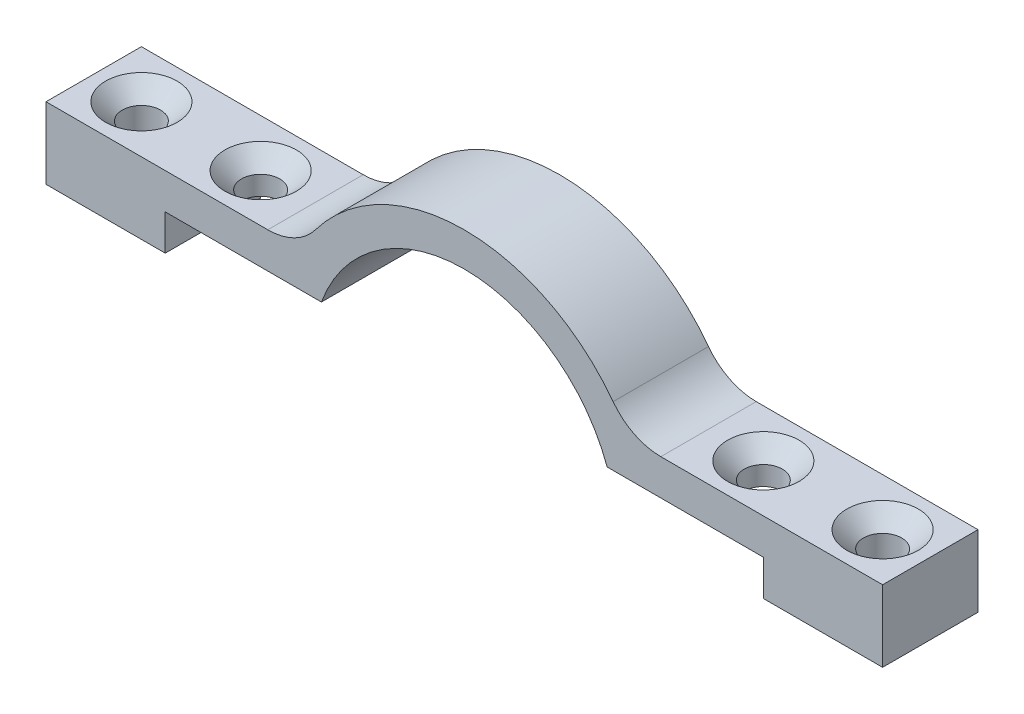
SolidWorks part; units mm, degrees
ref_plane "Front Plane" through (0, 0, 0) normal (0, 0, 1) x (1, 0, 0)
ref_plane "Top Plane" through (0, 0, 0) normal (0, 1, 0) x (1, 0, 0)
ref_plane "Right Plane" through (0, 0, 0) normal (1, 0, 0) x (0, 0, -1)
sketch "Sketch1" plane through (0, 0, 0) normal (0, 0, 1) x (1, 0, 0)
  line L0 (23.6887, 0) -> (-23.6887, 0) construction
  line L1 (-11.9811, 4.3608) -> (0, 0) construction
  line L2 (0, 0) -> (11.9811, 4.3608) construction
  line L3 (-14.9781, 4.3608) -> (-11.9811, 4.3608)
  line L4 (11.9811, 4.3608) -> (14.9781, 4.3608)
  line L5 (-14.9781, 4.3608) -> (-25.0781, 4.3608)
  line L6 (-25.0781, 4.3608) -> (-25.0781, 7.3608)
  line L7 (-25.0781, 7.3608) -> (-13.7542, 7.3608)
  line L8 (14.9781, 4.3608) -> (25.0781, 4.3608)
  line L9 (25.0781, 4.3608) -> (25.0781, 7.3608)
  line L10 (25.0781, 7.3608) -> (13.7542, 7.3608)
  line L11 (-25.0781, 4.3608) -> (-25.0781, 1.3608)
  line L12 (-25.0781, 1.3608) -> (-35.0781, 1.3608)
  line L13 (-35.0781, 1.3608) -> (-35.0781, 7.3608)
  line L16 (-35.0781, 7.3608) -> (-25.0781, 7.3608)
  line L17 (25.0781, 4.3608) -> (25.0781, 1.3608)
  line L18 (25.0781, 1.3608) -> (35.0781, 1.3608)
  line L19 (35.0781, 1.3608) -> (35.0781, 7.3608)
  line L22 (35.0781, 7.3608) -> (25.0781, 7.3608)
  arc A0 (11.9811, 4.3608) -> (-11.9811, 4.3608) centre (0, 0) ccw
  arc A1 (14.9781, 4.3608) -> (-14.9781, 4.3608) centre (0, 0) ccw
  point P4 (0, 0)
  dimension "D2" = 12.75
  dimension "D6" = 15.6
  dimension "D1" = 20
  dimension "D3" = 20
  dimension "D4" = 10.1
  dimension "D5" = 10.1
  dimension "D7" = 3
  dimension "D8" = 3
  dimension "D9" = 3
  dimension "D11" = 10
  dimension "D13" = 3
  dimension "D14" = 10
extrude "Boss-Extrude1" add sketch "Sketch1" along normal blind 8
sketch "Sketch2" plane through (0, 7.3608, 0) normal (0, 1, 0) x (1, 0, 0)
  line L0 (-21.0781, 0) -> (-21.0781, -8) construction
  line L1 (-35.0781, -8) -> (-35.0781, 0) construction
  line L2 (35.0781, -8) -> (35.0781, 0) construction
  line L4 (21.0781, 0) -> (21.0781, -8) construction
  line L10 (-35.0781, -8) -> (-13.7542, -8) construction
  line L11 (-35.0781, 0) -> (-13.7542, 0) construction
  line L12 (35.0781, -8) -> (13.7542, -8) construction
  line L13 (35.0781, 0) -> (13.7542, 0) construction
  point P6 (-21.0781, -4)
  point P17 (21.0781, -4)
  dimension "D1" = 14
  dimension "D3" = 14
sketch "Sketch5" plane through (0, 7.3608, 0) normal (0, 1, 0) x (1, 0, 0)
  line L0 (-31.0781, 0) -> (-31.0781, -8) construction
  line L3 (-35.0781, -8) -> (-35.0781, 0) construction
  line L5 (31.0781, 0) -> (31.0781, -8) construction
  line L7 (35.0781, -8) -> (35.0781, 0) construction
  line L8 (-35.0781, -8) -> (-13.7542, -8) construction
  line L9 (-35.0781, 0) -> (-13.7542, 0) construction
  line L10 (35.0781, -8) -> (13.7542, -8) construction
  line L11 (35.0781, 0) -> (13.7542, 0) construction
  point P12 (-31.0781, -4)
  point P13 (31.0781, -4)
  dimension "D1" = 4
  dimension "D3" = 4
hole_wizard "Hole1" positions "3DSketch2" profile "Sketch4" legacy end condition through all
sketch3d "3DSketch2"
  point P0 (-21.0781, 7.3608, 4)
  point P3 (21.0781, 7.3608, 4)
  point P7 (-31.0781, 7.3608, 4)
  point P10 (31.0781, 7.3608, 4)
sketch "Sketch4" plane through (-21.0781, 7.3608, 4) normal (1, 0, 0) x (0, 0, 1)
  line L0 (0, 0) -> (0, 6)
  line L1 (0, 6) -> (1.6, 6)
  line L2 (1.6, 6) -> (1.6, 1.4)
  line L3 (1.6, 1.4) -> (3, 0)
  line L4 (3, 0) -> (0, 0)
  line L5 (0, -6.4453) -> (0, 115.525) construction
  line L6 (-1.6, 1.4) -> (-3, 0) construction
  dimension "Diameter" = 3.2
  dimension "Depth" = 6
  dimension "C-Sink Angle" = 90
  dimension "C-Sink Diameter" = 6
fillet "Fillet1" radius 5 2 edges at (-13.7542, 7.3608, 4) (13.7542, 7.3608, 4)
